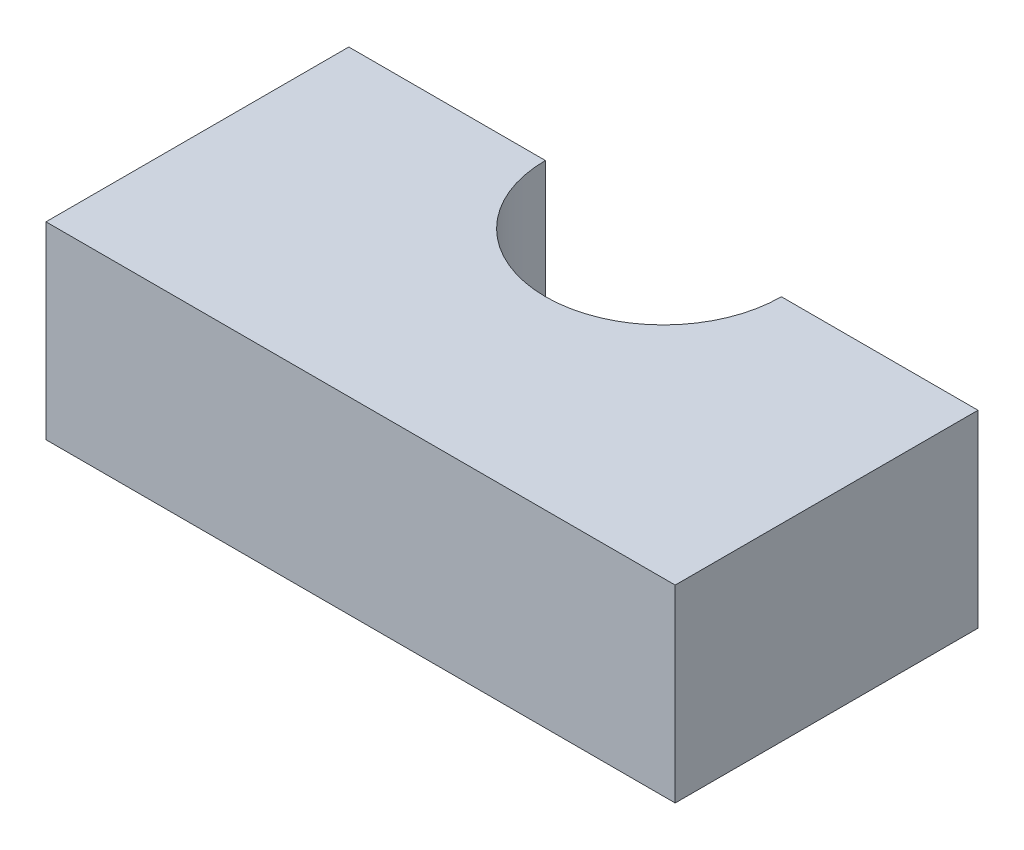
SolidWorks part; units mm, degrees
material "A-Glass Fiber"
ref_plane "Front Plane" through (0, 0, 0) normal (0, 0, 1) x (1, 0, 0)
ref_plane "Top Plane" through (0, 0, 0) normal (0, 1, 0) x (1, 0, 0)
ref_plane "Right Plane" through (0, 0, 0) normal (1, 0, 0) x (0, 0, -1)
sketch "Sketch1" plane through (0, 0, 0) normal (0, 1, 0) x (1, 0, 0)
  line L1 (-0.8, 0.385) -> (0.8, 0.385)
  line L2 (-0.8, 0.385) -> (-0.8, -0.385)
  line L3 (-0.8, -0.385) -> (0.8, -0.385)
  line L4 (0.8, 0.385) -> (0.8, -0.385)
  line L5 (-0.8, 0.385) -> (0.8, -0.385) construction
  line L6 (-0.8, -0.385) -> (0.8, 0.385) construction
  point P0 (0, 0)
  dimension "D1" = 1.6
  dimension "D2" = 0.77
extrude "Boss-Extrude1" add sketch "Sketch1" along normal blind 0.48
sketch "Sketch2" plane through (0, 0.48, 0) normal (0, 1, 0) x (1, 0, 0)
  line L0 (0.8, 0.385) -> (-0.8, 0.385) construction
  circle A0 centre (0, 0.385) radius 0.3
extrude "Cut-Extrude1" cut sketch "Sketch2" against normal through all
